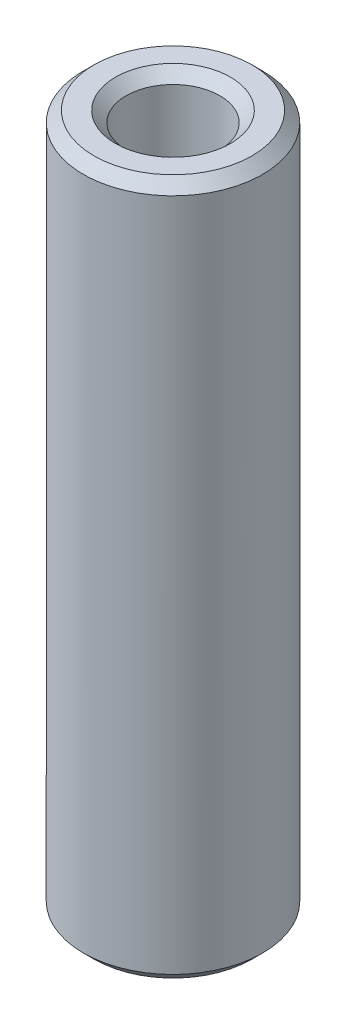
SolidWorks part; units mm, degrees
ref_plane "Front Plane" through (0, 0, 0) normal (0, 0, 1) x (1, 0, 0)
ref_plane "Top Plane" through (0, 0, 0) normal (0, 1, 0) x (1, 0, 0)
ref_plane "Right Plane" through (0, 0, 0) normal (1, 0, 0) x (0, 0, -1)
sketch "Sketch2" plane through (0, 0, 0) normal (0, 1, 0) x (1, 0, 0)
  circle A0 centre (0, 0) radius 1.75
  circle A1 centre (0, 0) radius 3.35
  dimension "D1" = 1.6
  dimension "D2" = 3.5
extrude "Boss-Extrude1" add sketch "Sketch2" along normal blind 26
chamfer "Chamfer1" distance 0.4 angle 45 4 edges at (0, 0, 3.35) (0, 0, 1.75) (0, 26, 3.35) (0, 26, 1.75)
